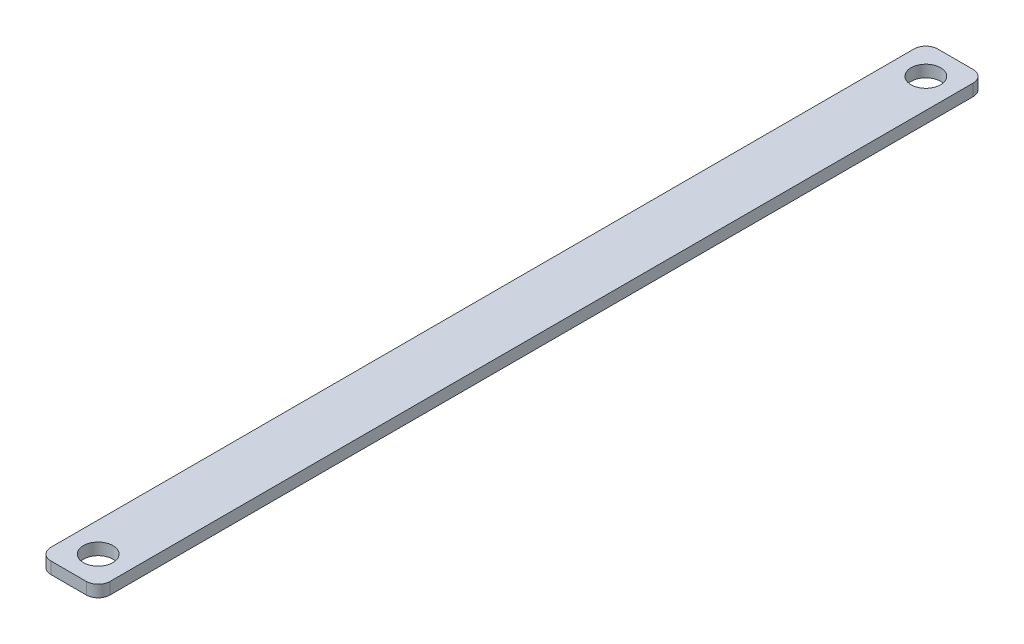
SolidWorks part; units mm, degrees
ref_plane "Front Plane" through (0, 0, 0) normal (0, 0, 1) x (1, 0, 0)
ref_plane "Top Plane" through (0, 0, 0) normal (0, 1, 0) x (1, 0, 0)
ref_plane "Right Plane" through (0, 0, 0) normal (1, 0, 0) x (0, 0, -1)
sketch "Sketch1" plane through (0, 0, 0) normal (0, 1, 0) x (1, 0, 0)
  line L1 (10, 0) -> (40, 0)
  line L2 (0, 10) -> (0, 740)
  line L3 (10, 750) -> (40, 750)
  line L4 (50, 10) -> (50, 740)
  arc A0 (40, 0) -> (50, 10) centre (40, 10) ccw
  arc A1 (10, 0) -> (0, 10) centre (10, 10) cw
  arc A2 (0, 740) -> (10, 750) centre (10, 740) cw
  arc A3 (40, 750) -> (50, 740) centre (40, 740) cw
  circle A4 centre (25, 25) radius 12.5
  circle A5 centre (25, 725) radius 12.5
  point P7 (50, 0)
  point P10 (0, 0)
  point P13 (0, 750)
  point P16 (50, 750)
  dimension "D3" = 10
  dimension "D4" = 25
  dimension "D1" = 750
  dimension "D2" = 50
  dimension "D5" = 25
  dimension "D6" = 25
  dimension "D7" = 25
extrude "Boss-Extrude1" add sketch "Sketch1" along normal blind 10
equation "\"D6@Sketch1\"=\"D5@Sketch1\""
